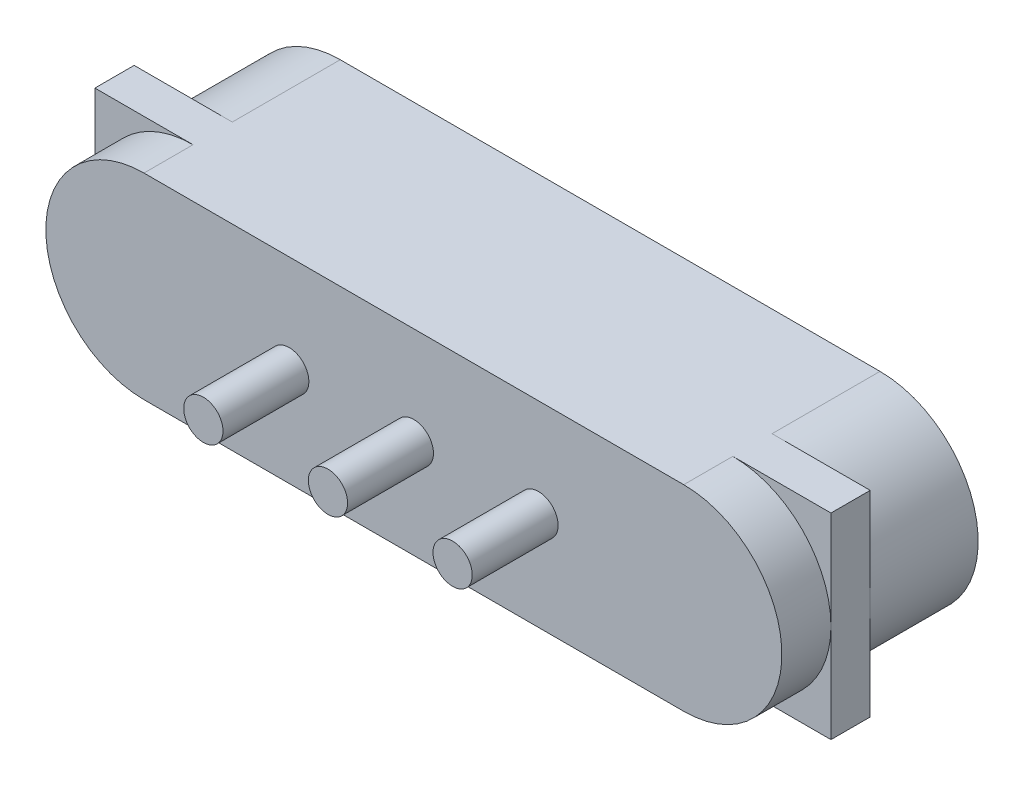
SolidWorks part; units mm, degrees
ref_plane "前视基准面" through (0, 0, 0) normal (0, 0, 1) x (1, 0, 0)
ref_plane "上视基准面" through (0, 0, 0) normal (0, 1, 0) x (1, 0, 0)
ref_plane "右视基准面" through (0, 0, 0) normal (1, 0, 0) x (0, 0, -1)
sketch "草图1" plane through (0, 0, 0) normal (0, 0, 1) x (1, 0, 0)
  line L0 (0, 0) -> (11, 0) construction
  line L1 (0, 2) -> (11, 2)
  line L2 (0, -2) -> (11, -2)
  arc A0 (0, 2) -> (0, -2) centre (0, 0) ccw
  arc A1 (11, -2) -> (11, 2) centre (11, 0) ccw
  point P3 (5.5, 0)
  point P8 (-2, 0)
  point P9 (13, 0)
  dimension "D1" = 15
  dimension "D2" = 4
extrude "凸台-拉伸1" add sketch "草图1" along normal blind 4
sketch "草图2" plane through (0, 0, 0) normal (0, 0, -1) x (-1, 0, 0)
  line L0 (-11, 2) -> (0, 2) construction
  line L1 (-13, 2) -> (2, 2)
  line L2 (-13, 2) -> (-13, -2)
  line L3 (-13, -2) -> (2, -2)
  line L4 (2, 2) -> (2, -2)
  line L5 (0, -2) -> (-11, -2) construction
  arc A0 (-11, 2) -> (-11, -2) centre (-11, 0) ccw construction
  arc A1 (0, -2) -> (0, 2) centre (0, 0) ccw construction
extrude "凸台-拉伸2" add sketch "草图2" against normal blind 0.8 from offset 2.2 offset against normal yes
sketch "草图3" plane through (0, 0, 0) normal (0, 0, -1) x (-1, 0, 0)
  line L0 (-11, 2) -> (0, 2) construction
  circle A0 centre (-8.04, 0) radius 0.5
  circle A1 centre (-5.5, 0) radius 0.5
  circle A2 centre (-2.96, 0) radius 0.5
  point P8 (-5.5, 2)
  dimension "D1" = 1
  dimension "D2" = 1
  dimension "D3" = 1
  dimension "D4" = 2.54
  dimension "D5" = 2.54
extrude "凸台-拉伸3" add sketch "草图3" along normal blind 1
fillet "圆角1" radius 0.5 3 edges at (7.54, 0, -1) (5, 0, -1) (2.46, 0, -1)
sketch "草图4" plane through (0, 0, 4) normal (0, 0, 1) x (1, 0, 0)
  circle A95 centre (2.96, 0) radius 0.4
  circle A96 centre (2.96, 0) radius 0.4
  circle A99 centre (5.5, 0) radius 0.4
  circle A100 centre (5.5, 0) radius 0.4
  circle A102 centre (8.04, 0) radius 0.4
  circle A103 centre (8.04, 0) radius 0.4
  dimension "D2" = 0.1
  dimension "D1" = 0.1
  dimension "D3" = 0.1
extrude "凸台-拉伸4" add sketch "草图4" along normal blind 1.75
ref_plane "基准面1" through (5.5, 0, 0) normal (-1, 0, 0) x (0, 0, 1)
